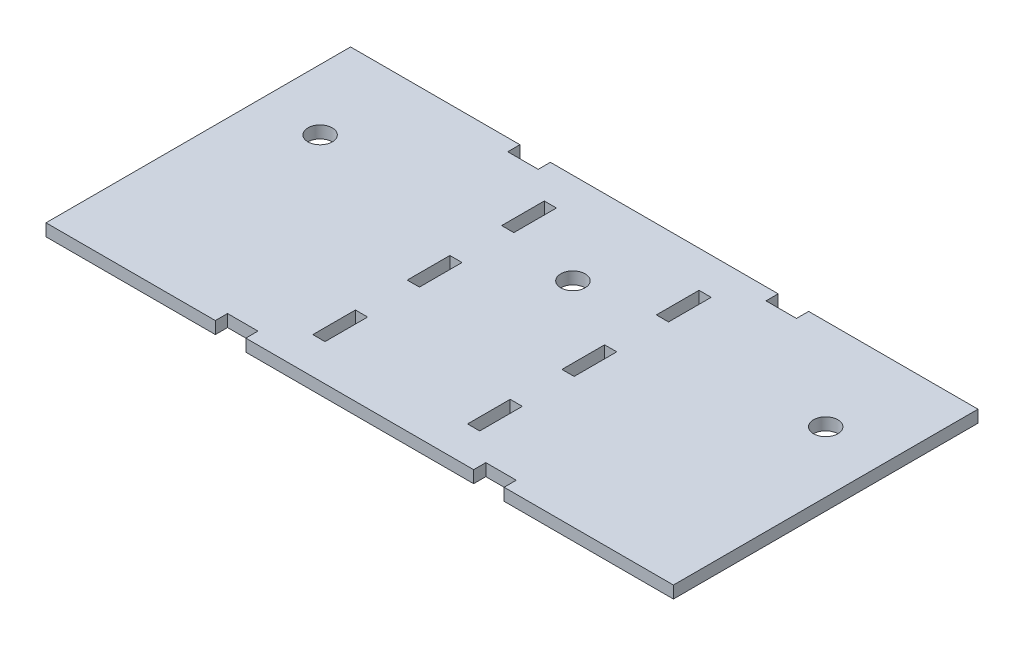
SolidWorks part; units mm, degrees
ref_plane "Front Plane" through (0, 0, 0) normal (0, 0, 1) x (1, 0, 0)
ref_plane "Top Plane" through (0, 0, 0) normal (0, 1, 0) x (1, 0, 0)
ref_plane "Right Plane" through (0, 0, 0) normal (1, 0, 0) x (0, 0, -1)
sketch "Sketch1" plane through (0, 0, 0) normal (0, 1, 0) x (1, 0, 0)
  line L0 (-30.9995, -41.9807) -> (-32.9995, -41.9807)
  line L1 (-70.7995, 2.0193) -> (32.2005, 2.0193)
  line L2 (-70.7995, 2.0193) -> (-70.7995, -47.9807)
  line L3 (-70.7995, -47.9807) -> (32.2005, -47.9807)
  line L4 (32.2005, 2.0193) -> (32.2005, -47.9807)
  line L5 (-30.9995, -41.9807) -> (-30.9995, -34.9807)
  line L6 (-30.9995, -34.9807) -> (-32.9995, -34.9807)
  line L7 (-32.9995, -41.9807) -> (-32.9995, -34.9807)
  line L8 (-30.9995, -26.4807) -> (-32.9995, -26.4807)
  line L9 (-30.9995, -26.4807) -> (-30.9995, -19.4807)
  line L10 (-30.9995, -19.4807) -> (-32.9995, -19.4807)
  line L11 (-32.9995, -26.4807) -> (-32.9995, -19.4807)
  line L12 (-30.9995, -10.9807) -> (-32.9995, -10.9807)
  line L13 (-30.9995, -10.9807) -> (-30.9995, -3.9807)
  line L14 (-30.9995, -3.9807) -> (-32.9995, -3.9807)
  line L15 (-32.9995, -10.9807) -> (-32.9995, -3.9807)
  line L16 (-5.5995, -10.9807) -> (-7.5995, -10.9807)
  line L17 (-5.5995, -10.9807) -> (-5.5995, -3.9807)
  line L18 (-5.5995, -3.9807) -> (-7.5995, -3.9807)
  line L19 (-7.5995, -10.9807) -> (-7.5995, -3.9807)
  line L20 (-5.5995, -26.4807) -> (-7.5995, -26.4807)
  line L21 (-5.5995, -26.4807) -> (-5.5995, -19.4807)
  line L22 (-5.5995, -19.4807) -> (-7.5995, -19.4807)
  line L23 (-7.5995, -26.4807) -> (-7.5995, -19.4807)
  line L24 (-5.5995, -41.9807) -> (-7.5995, -41.9807)
  line L25 (-5.5995, -41.9807) -> (-5.5995, -34.9807)
  line L26 (-5.5995, -34.9807) -> (-7.5995, -34.9807)
  line L27 (-7.5995, -41.9807) -> (-7.5995, -34.9807)
  line L29 (-42.9995, -47.9807) -> (-37.9995, -47.9807)
  line L30 (-42.9995, -47.9807) -> (-42.9995, -45.9807)
  line L31 (-42.9995, -45.9807) -> (-37.9995, -45.9807)
  line L32 (-37.9995, -47.9807) -> (-37.9995, -45.9807)
  line L33 (-0.5995, -47.9807) -> (4.4005, -47.9807)
  line L34 (-0.5995, -47.9807) -> (-0.5995, -45.9807)
  line L35 (-0.5995, -45.9807) -> (4.4005, -45.9807)
  line L36 (4.4005, -47.9807) -> (4.4005, -45.9807)
  line L37 (-42.9995, 2.0193) -> (-37.9995, 2.0193)
  line L38 (-42.9995, 2.0193) -> (-42.9995, 0.0193)
  line L39 (-42.9995, 0.0193) -> (-37.9995, 0.0193)
  line L40 (-37.9995, 2.0193) -> (-37.9995, 0.0193)
  line L41 (-0.5995, 2.0193) -> (4.4005, 2.0193)
  line L42 (-0.5995, 2.0193) -> (-0.5995, 0.0193)
  line L43 (-0.5995, 0.0193) -> (4.4005, 0.0193)
  line L44 (4.4005, 2.0193) -> (4.4005, 0.0193)
  circle A0 centre (-60.7995, -12.9807) radius 2
  circle A1 centre (22.2005, -12.9807) radius 2
  circle A2 centre (-19.2995, -12.9807) radius 2
  dimension "D21" = 4
  dimension "D22" = 4
  dimension "D24" = 23.4
  dimension "D25" = 23.4
  dimension "D27" = 15
  dimension "D29" = 4
  dimension "D31" = 51.5
  dimension "D1" = 50
  dimension "D2" = 103
  dimension "D4" = 7
  dimension "D5" = 2
  dimension "D6" = 7
  dimension "D7" = 2
  dimension "D8" = 7
  dimension "D9" = 2
  dimension "D10" = 7
  dimension "D11" = 2
  dimension "D12" = 7
  dimension "D13" = 2
  dimension "D14" = 7
  dimension "D15" = 2
  dimension "D16" = 8.5
  dimension "D17" = 8.5
  dimension "D18" = 8.5
  dimension "D19" = 8.5
  dimension "D20" = 23.4
  dimension "D23" = 10
  dimension "D26" = 10
  dimension "D28" = 15
  dimension "D30" = 15
  dimension "D32" = 0
  dimension "D33" = 0
  dimension "D34" = 0
  dimension "D35" = 6
  dimension "D36" = 6
  dimension "D37" = 6
  dimension "D38" = 6
  dimension "D39" = 37.8
  dimension "D40" = 37.8
  dimension "D41" = 11.7
  dimension "D42" = 11.7
  dimension "D43" = 2
  dimension "D44" = 5
  dimension "D45" = 5
  dimension "D46" = 2
  dimension "D47" = 5
  dimension "D48" = 5
  dimension "D49" = 5
  dimension "D50" = 5
  dimension "D51" = 2
  dimension "D52" = 5
  dimension "D53" = 5
  dimension "D54" = 2
extrude "Boss-Extrude1" add sketch "Sketch1" along normal blind 2 contours L1 L44 L43 L42 L40 L39 L38 L2 L3 L30 L31 L32 L34 L35 L36 L4 A2 A1 A0 L0 L7 L6 L5 L8 L11 L10 L9 L12 L15 L14 L13 L16 L19 L18 L17 L20 L23 L22 L21
